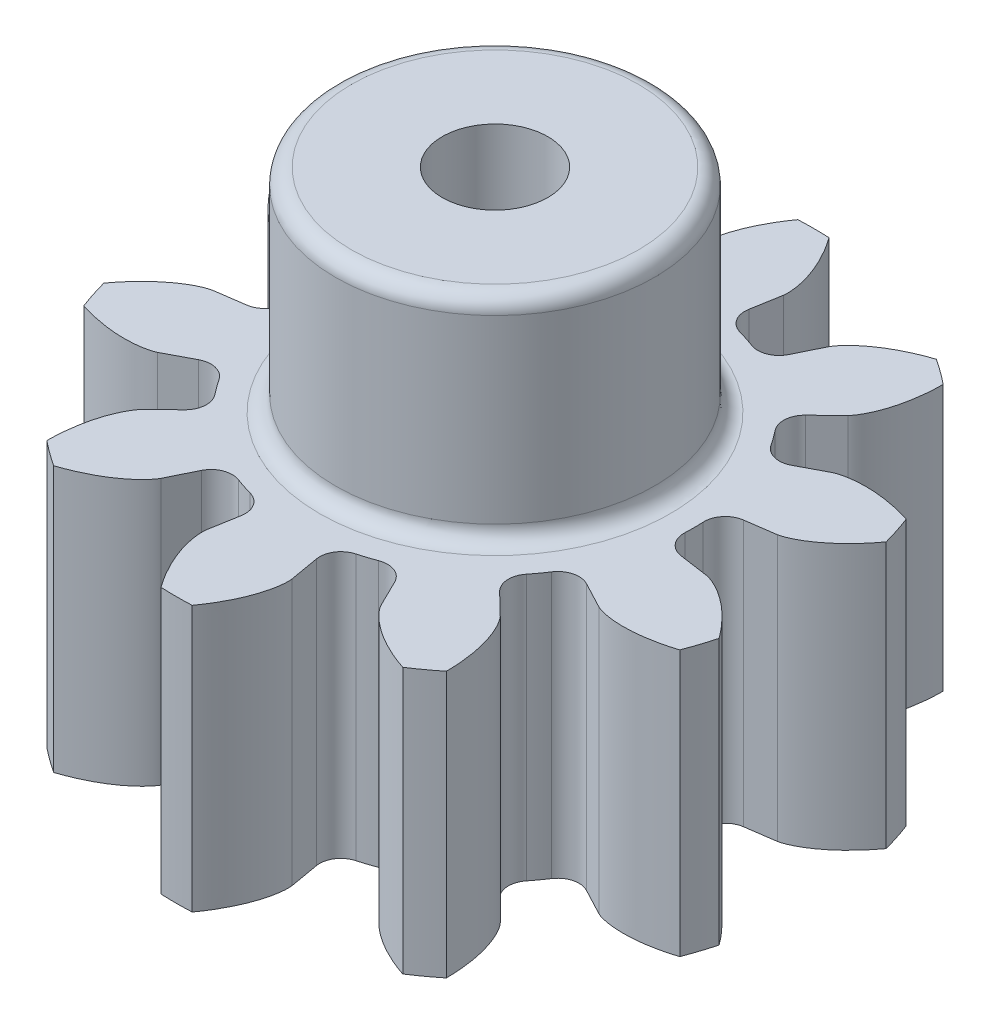
SolidWorks part; units mm, degrees
ref_plane "Front Plane" through (0, 0, 0) normal (0, 0, 1) x (1, 0, 0)
ref_plane "Top Plane" through (0, 0, 0) normal (0, 1, 0) x (1, 0, 0)
ref_plane "Right Plane" through (0, 0, 0) normal (1, 0, 0) x (0, 0, -1)
sketch "Sketch2" plane through (0, 0, 0) normal (0, 1, 0) x (1, 0, 0)
  circle A0 centre (0, 0) radius 15.24
  dimension "D1" = 30.48
extrude "Boss-Extrude1" add sketch "Sketch2" along normal blind 12.7
sketch "Sketch3" plane through (0, 0, 0) normal (0, -1, 0) x (-1, 0, 0)
  line L0 (0, 0) -> (11.8137, -1.691) construction
  line L1 (0, 0) -> (11.8137, 1.691) construction
  line L2 (11.8137, -1.691) -> (9.4289, -1.3497)
  line L3 (11.8137, 1.691) -> (9.4289, 1.3497)
  circle A0 centre (0, 0) radius 15.24
  circle A1 centre (0, 0) radius 12.7
  circle A2 centre (0, 0) radius 11.938
  circle A3 centre (0, 0) radius 9.525
  arc A4 (14.7073, 3.9942) -> (14.7073, -3.9942) centre (0, 0) cw
  arc A5 (9.4289, 1.3497) -> (9.4289, -1.3497) centre (0, 0) cw
  spline S0 degree 4 poles (11.8137, 1.691) (11.8192, 1.6919) (11.8345, 1.6947) (11.8634, 1.701) (11.9102, 1.7129) (11.9692, 1.7305) (12.0448, 1.7558) (12.1329, 1.789) (12.2286, 1.829) (12.3315, 1.8763) (12.433, 1.9267) (12.5329, 1.9801) (12.6314, 2.036) (12.7494, 2.1069) (12.8888, 2.1963) (13.0487, 2.3071) (13.2263, 2.4402) (13.4031, 2.5835) (13.5735, 2.7307) (13.7413, 2.8866) (13.9005, 3.0423) (14.0612, 3.2111) (14.2071, 3.3705) (14.3651, 3.5565) (14.4911, 3.7088) (14.6511, 3.9175) (14.7439, 4.0431) (14.8502, 4.1926) (14.8963, 4.2604) (14.9247, 4.3021) knots 0 0 0 0 0 0.005377 0.015084 0.028532 0.04661 0.064855 0.092111 0.119476 0.146842 0.174209 0.201575 0.228941 0.256307 0.307035 0.361767 0.4165 0.471232 0.525964 0.580697 0.635429 0.690161 0.744894 0.799626 0.854358 0.909091 0.954545 1 1 1 1 1 construction
  spline S1 degree 4 poles (11.8137, 1.691) (11.8192, 1.6919) (11.8345, 1.6947) (11.8634, 1.701) (11.9102, 1.7129) (11.9692, 1.7305) (12.0448, 1.7558) (12.1329, 1.789) (12.2286, 1.829) (12.3315, 1.8763) (12.433, 1.9267) (12.5329, 1.9801) (12.6314, 2.036) (12.7494, 2.1069) (12.8888, 2.1963) (13.0487, 2.3071) (13.2263, 2.4402) (13.4031, 2.5835) (13.5735, 2.7307) (13.7413, 2.8866) (13.9005, 3.0423) (14.0612, 3.2111) (14.2071, 3.3705) (14.3651, 3.5565) (14.4911, 3.7088) (14.6164, 3.8723) (14.6768, 3.9527) (14.7073, 3.9942) knots 0 0 0 0 0 0.005377 0.015084 0.028532 0.04661 0.064855 0.092111 0.119476 0.146842 0.174209 0.201575 0.228941 0.256307 0.307035 0.361767 0.4165 0.471232 0.525964 0.580697 0.635429 0.690161 0.744894 0.799626 0.854358 0.909091 0.909091 0.909091 0.909091 0.909091
  spline S2 degree 4 poles (11.8137, -1.691) (11.8192, -1.6919) (11.8345, -1.6947) (11.8634, -1.701) (11.9102, -1.7129) (11.9692, -1.7305) (12.0448, -1.7558) (12.1329, -1.789) (12.2286, -1.829) (12.3315, -1.8763) (12.433, -1.9267) (12.5329, -1.9801) (12.6314, -2.036) (12.7494, -2.1069) (12.8888, -2.1963) (13.0487, -2.3071) (13.2263, -2.4402) (13.4031, -2.5835) (13.5735, -2.7307) (13.7413, -2.8866) (13.9005, -3.0423) (14.0612, -3.2111) (14.2071, -3.3705) (14.3651, -3.5565) (14.4911, -3.7088) (14.6511, -3.9175) (14.7439, -4.0431) (14.8502, -4.1926) (14.8963, -4.2604) (14.9247, -4.3021) knots 0 0 0 0 0 0.005377 0.015084 0.028532 0.04661 0.064855 0.092111 0.119476 0.146842 0.174209 0.201575 0.228941 0.256307 0.307035 0.361767 0.4165 0.471232 0.525964 0.580697 0.635429 0.690161 0.744894 0.799626 0.854358 0.909091 0.954545 1 1 1 1 1 construction
  spline S3 degree 4 poles (11.8137, -1.691) (11.8192, -1.6919) (11.8345, -1.6947) (11.8634, -1.701) (11.9102, -1.7129) (11.9692, -1.7305) (12.0448, -1.7558) (12.1329, -1.789) (12.2286, -1.829) (12.3315, -1.8763) (12.433, -1.9267) (12.5329, -1.9801) (12.6314, -2.036) (12.7494, -2.1069) (12.8888, -2.1963) (13.0487, -2.3071) (13.2263, -2.4402) (13.4031, -2.5835) (13.5735, -2.7307) (13.7413, -2.8866) (13.9005, -3.0423) (14.0612, -3.2111) (14.2071, -3.3705) (14.3651, -3.5565) (14.4911, -3.7088) (14.6164, -3.8723) (14.6768, -3.9527) (14.7073, -3.9942) knots 0 0 0 0 0 0.005377 0.015084 0.028532 0.04661 0.064855 0.092111 0.119476 0.146842 0.174209 0.201575 0.228941 0.256307 0.307035 0.361767 0.4165 0.471232 0.525964 0.580697 0.635429 0.690161 0.744894 0.799626 0.854358 0.909091 0.909091 0.909091 0.909091 0.909091
  circle M5 centre (0, 0) radius 15.24
  dimension "D1" = 30.48
  dimension "D2" = 25.4
  dimension "D3" = 23.876
  dimension "D4" = 19.05
extrude "Cut-Extrude1" cut sketch "Sketch3" against normal through all contours A1 S3 S1 M5 | A2 S3 A1 S1 | L2 S3 A2 S1 L3 A3
fillet "Fillet1" radius 1.016 2 edges at (-9.4289, 6.35, -1.3497) (-9.4289, 6.35, 1.3497)
pattern_circular "CirPattern1" count 10 over 360 about axis through (0, 0, 0) along (0, 1, 0) of "Fillet1", "Cut-Extrude1"
sketch "Sketch4" plane through (0, 12.7, 0) normal (0, 1, 0) x (1, 0, 0)
  circle A0 centre (0, 0) radius 2.525
  circle A1 centre (0, 0) radius 7.62
  dimension "D1" = 5.05
  dimension "D2" = 15.24
extrude "Boss-Extrude2" add sketch "Sketch4" along normal blind 10.16
sketch "Sketch5" plane through (0, 12.7, 0) normal (0, 1, 0) x (1, 0, 0)
  circle A0 centre (0, 0) radius 2.525
extrude "Cut-Extrude2" cut sketch "Sketch5" against normal through all
fillet "Fillet2" radius 0.762 2 edges at (0, 22.86, 7.62) (0, 12.7, 7.62)
equation "\"DiametralPitch\"= 10"
equation "\"NumTeeth\"= 10"
equation "\"PressureAngle\"= 20deg"
equation "\"Addendum\"= 1 / \"DiametralPitch\""
equation "\"Dedendum\"= 1.25 / \"DiametralPitch\""
equation "\"WorkingDepth\"= 2 / \"DiametralPitch\""
equation "\"WholeDepth\"= 2.25 / \"DiametralPitch\""
equation "\"Clearance\"= 0.3 / \"DiametralPitch\""
equation "\"ToothThickness\"= 1.5708 / \"DiametralPitch\""
equation "\"CircularPitch\"= pi / \"DiametralPitch\""
equation "\"PitchCircle\"= \"NumTeeth\" / \"DiametralPitch\""
equation "\"OutsideDiameter\"= ( \"NumTeeth\" + 2 ) / \"DiametralPitch\""
equation "\"Fillet\"= \"Clearance\" * cos ( \"PressureAngle\" ) * tan ( ( 90 + \"PressureAngle\" ) / 2 )"
equation "\"AddendumCircle\"= \"PitchCircle\" + ( 2 * \"Addendum\" )"
equation "\"DedendumCircle\"= \"PitchCircle\" - ( 2 * \"Dedendum\" )"
equation "\"BaseCircle\"= \"PitchCircle\" * cos ( \"PressureAngle\" )"
equation "\"PitchAngle\"= 360deg / \"NumTeeth\""
equation "\"Alpha\"= sqr ( \"PitchCircle\" ^ 2 - \"BaseCircle\" ^ 2 ) / \"BaseCircle\" * 180 / PI - \"PressureAngle\""
equation "\"Beta\"= ( \"PitchAngle\" / 4 - \"Alpha\" )"
equation "\"Phi\"= sqr ( ( \"AddendumCircle\" / 2 ) ^ 2 - ( \"BaseCircle\" / 2 ) ^ 2 ) / ( \"BaseCircle\" / 2 )"
